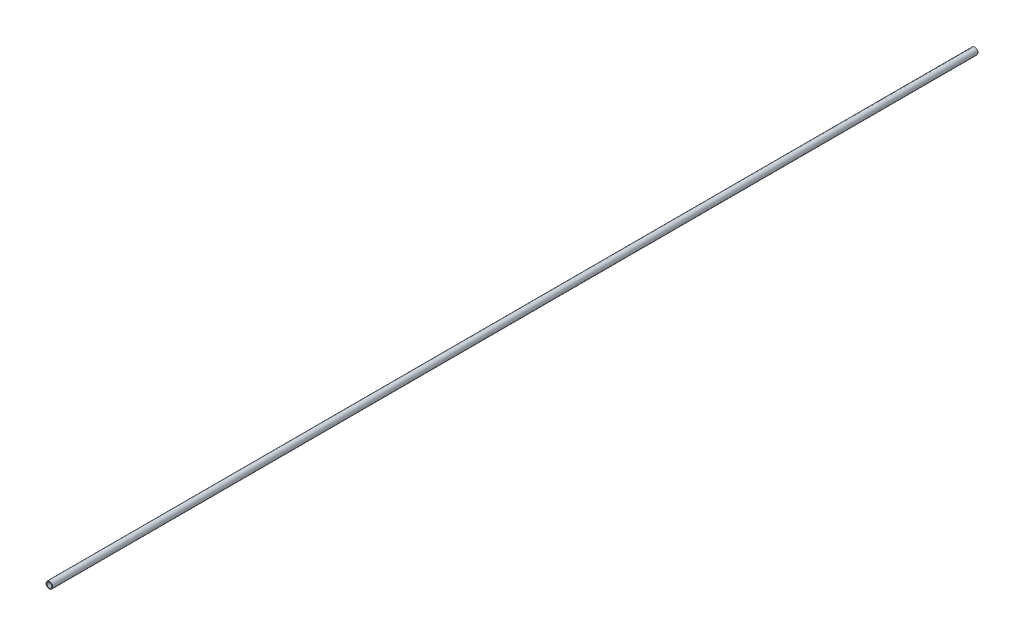
SolidWorks part; units mm, degrees
ref_plane "Front Plane" through (0, 0, 0) normal (0, 0, 1) x (1, 0, 0)
ref_plane "Top Plane" through (0, 0, 0) normal (0, 1, 0) x (1, 0, 0)
ref_plane "Right Plane" through (0, 0, 0) normal (1, 0, 0) x (0, 0, -1)
sketch "Sketch1" plane through (0, 0, 0) normal (0, 0, 1) x (1, 0, 0)
  circle A0 centre (0, 0) radius 10.668
  dimension "Pipe OD" = 21.336
extrude "Extrude-Thin1" add sketch "Sketch1" along normal mid plane 3000 thin thin type one direction reverse wall 2.7686
